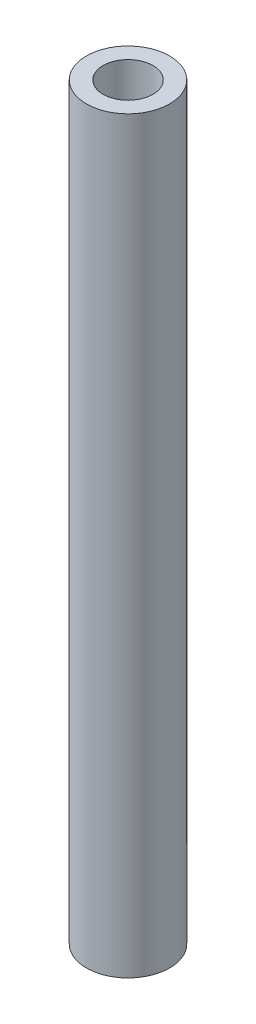
SolidWorks part; units mm, degrees
material "1060 Alloy"
ref_plane "Front Plane" through (0, 0, 0) normal (0, 0, 1) x (1, 0, 0)
ref_plane "Top Plane" through (0, 0, 0) normal (0, 1, 0) x (1, 0, 0)
ref_plane "Right Plane" through (0, 0, 0) normal (1, 0, 0) x (0, 0, -1)
sketch "Sketch1" plane through (0, 0, 0) normal (0, 1, 0) x (1, 0, 0)
  circle A0 centre (0, 0) radius 2.5
  circle A1 centre (0, 0) radius 1.5
  dimension "D1" = 5
  dimension "D2" = 3
extrude "Boss-Extrude1" add sketch "Sketch1" along normal blind 45
